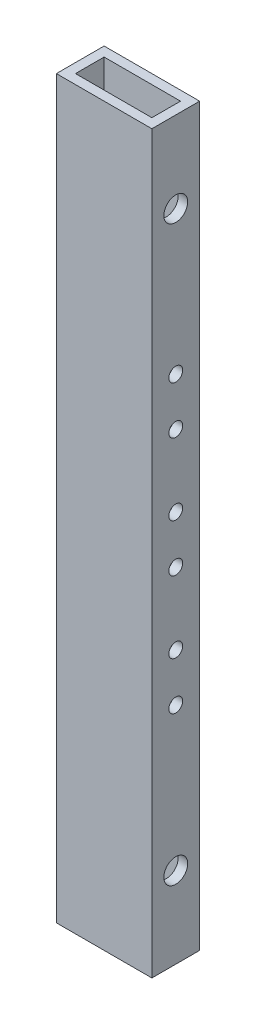
SolidWorks part; units mm, degrees
ref_plane "前视基准面" through (0, 0, 0) normal (0, 0, 1) x (1, 0, 0)
ref_plane "上视基准面" through (0, 0, 0) normal (0, 1, 0) x (1, 0, 0)
ref_plane "右视基准面" through (0, 0, 0) normal (1, 0, 0) x (0, 0, -1)
sketch "草图1" plane through (0, 0, 0) normal (0, 1, 0) x (1, 0, 0)
  line L1 (-10, 5) -> (10, 5)
  line L2 (-10, 5) -> (-10, -5)
  line L3 (-10, -5) -> (10, -5)
  line L4 (10, 5) -> (10, -5)
  line L5 (-10, 5) -> (10, -5) construction
  line L6 (-10, -5) -> (10, 5) construction
  line L7 (-8, 3) -> (8, 3)
  line L8 (-8, 3) -> (-8, -3)
  line L9 (-8, -3) -> (8, -3)
  line L10 (8, 3) -> (8, -3)
  line L11 (-8, 3) -> (8, -3) construction
  line L12 (-8, -3) -> (8, 3) construction
  point P0 (0, 0)
  point P6 (0, 0)
  dimension "D1" = 10
  dimension "D2" = 20
  dimension "D3" = 2
  dimension "D4" = 2
extrude "凸台-拉伸1" add sketch "草图1" along normal mid plane 154
sketch "草图2" plane through (10, 0, 0) normal (1, 0, 0) x (0, 0, -1)
  line L0 (0, 0) -> (0, -17.282) construction
  line L1 (0, 0) -> (-14.5337, 0) construction
  circle A0 centre (0, 5) radius 1.45
  circle A1 centre (0, 20) radius 1.45
  circle A2 centre (0, 30) radius 1.45
  circle A3 centre (0, -30) radius 1.45
  circle A4 centre (0, -20) radius 1.45
  circle A5 centre (0, -5) radius 1.45
  circle A6 centre (0, 60) radius 2.5
  circle A7 centre (0, -60) radius 2.5
  dimension "D4" = 2.9
  dimension "D5" = 5
  dimension "D1" = 5
  dimension "D2" = 10
  dimension "D3" = 15
  dimension "D6" = 30
extrude "切除-拉伸1" cut sketch "草图2" against normal through all
